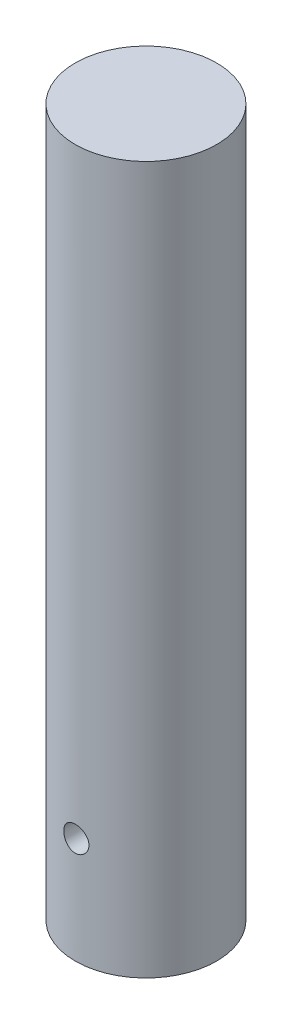
SolidWorks part; units mm, degrees
material "6061 Alloy"
ref_plane "Front Plane" through (0, 0, 0) normal (0, 0, 1) x (1, 0, 0)
ref_plane "Top Plane" through (0, 0, 0) normal (0, 1, 0) x (1, 0, 0)
ref_plane "Right Plane" through (0, 0, 0) normal (1, 0, 0) x (0, 0, -1)
sketch "Sketch1" plane through (0, 0, 0) normal (0, 1, 0) x (1, 0, 0)
  circle A0 centre (0, 0) radius 6.35
  dimension "D1" = 12.7
extrude "Boss-Extrude1" add sketch "Sketch1" along normal blind 63.5 contours A0
sketch "Sketch2" plane through (0, 0, 0) normal (0, 1, 0) x (1, 0, 0)
  circle A0 centre (0, 0) radius 3.175
  dimension "D1" = 6.35
extrude "Cut-Extrude1" cut sketch "Sketch2" along normal blind 19.05 contours A0
hole_wizard "#43 (0.089) Diameter Hole1" positions "Sketch4" profile "Sketch5" hole size "#43" standard "ANSI Inch"
sketch "Sketch4" plane through (0, 0, 0) normal (0, 0, 1) x (1, 0, 0)
  line L0 (-6.35, 0) -> (6.35, 0) construction
  point P0 (0, 9.525)
  dimension "D1" = 9.525
sketch "Sketch5" plane through (0, 9.525, 0) normal (1, 0, 0) x (0, 1, 0)
  line L0 (0, 0) -> (0, 6.35)
  line L1 (0, 6.35) -> (1.1303, 6.35)
  line L2 (1.1303, 6.35) -> (1.1303, 0)
  line L5 (1.1303, 0) -> (0, 0)
  line L11 (0, -6.35) -> (0, 107.95) construction
  dimension "Thru Hole Dia." = 2.2606
  dimension "Thru Hole Depth" = 6.35
